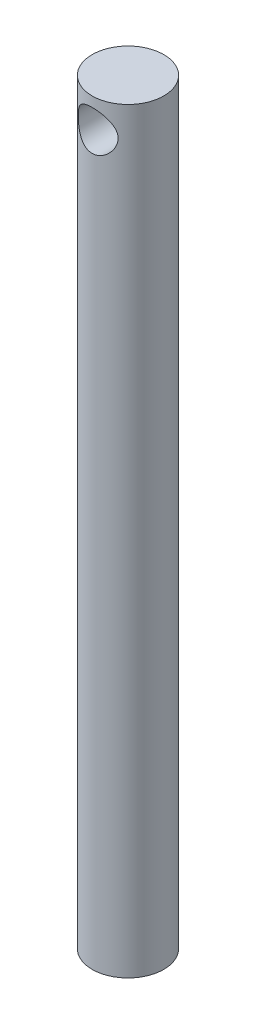
SolidWorks part; units mm, degrees
ref_plane "Front Plane" through (0, 0, 0) normal (0, 0, 1) x (1, 0, 0)
ref_plane "Top Plane" through (0, 0, 0) normal (0, 1, 0) x (1, 0, 0)
ref_plane "Right Plane" through (0, 0, 0) normal (1, 0, 0) x (0, 0, -1)
sketch "Szkic1" plane through (0, 0, 0) normal (0, 1, 0) x (1, 0, 0)
  circle A0 centre (0, 0) radius 0.9
  dimension "D1" = 1.8
extrude "Dodanie-wyciągnięcie1" add sketch "Szkic1" along normal blind 19
sketch "Szkic2" plane through (0, 0, 0) normal (0, 0, 1) x (1, 0, 0)
  line L0 (0.9, 19) -> (-0.9, 19) construction
  circle A0 centre (0, 18.25) radius 0.5
  dimension "D1" = 1
  dimension "D2" = 0.75
extrude "Wytnij-wyciągnięcie1" cut sketch "Szkic2" against normal through all both and the other way through all
